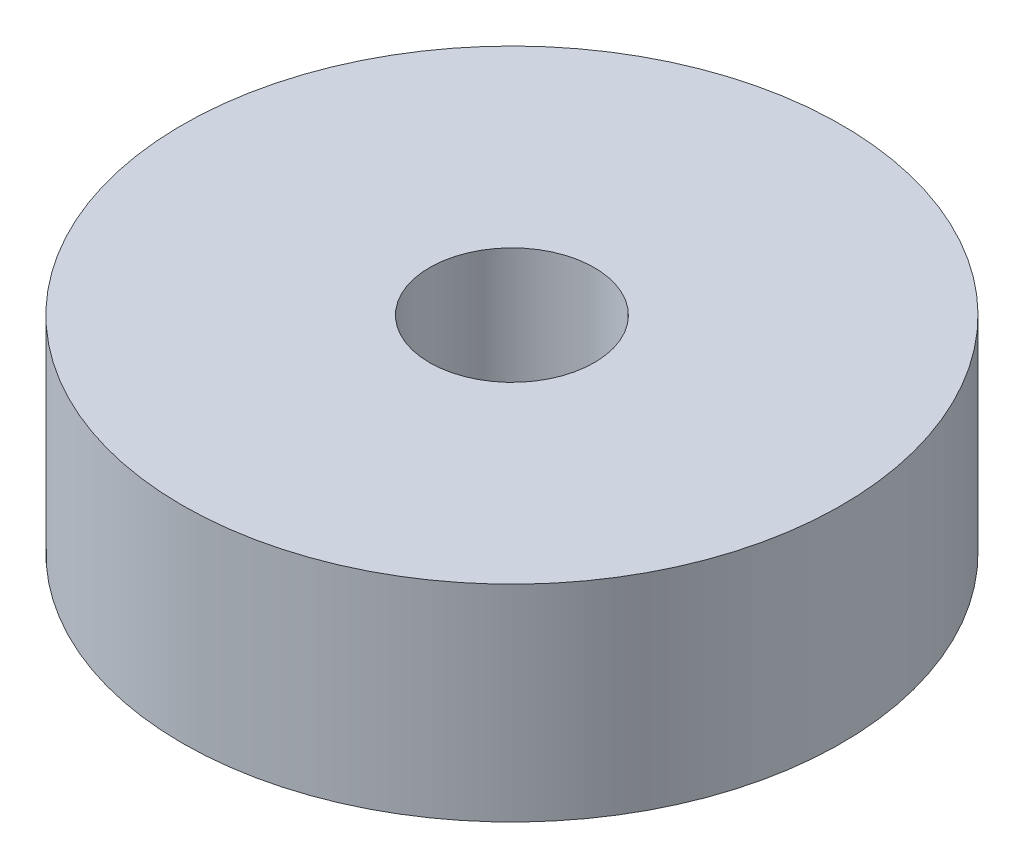
SolidWorks part; units mm, degrees
ref_plane "Front" through (0, 0, 0) normal (0, 0, 1) x (1, 0, 0)
ref_plane "Top" through (0, 0, 0) normal (0, 1, 0) x (1, 0, 0)
ref_plane "Right" through (0, 0, 0) normal (1, 0, 0) x (0, 0, -1)
sketch "草图1" plane through (0, 0, 0) normal (0, 1, 0) x (1, 0, 0)
  circle A0 centre (0, 0) radius 2
  circle A1 centre (0, 0) radius 8
  dimension "D1" = 4
  dimension "D2" = 16
extrude "凸台-拉伸1" add sketch "草图1" along normal blind 5
